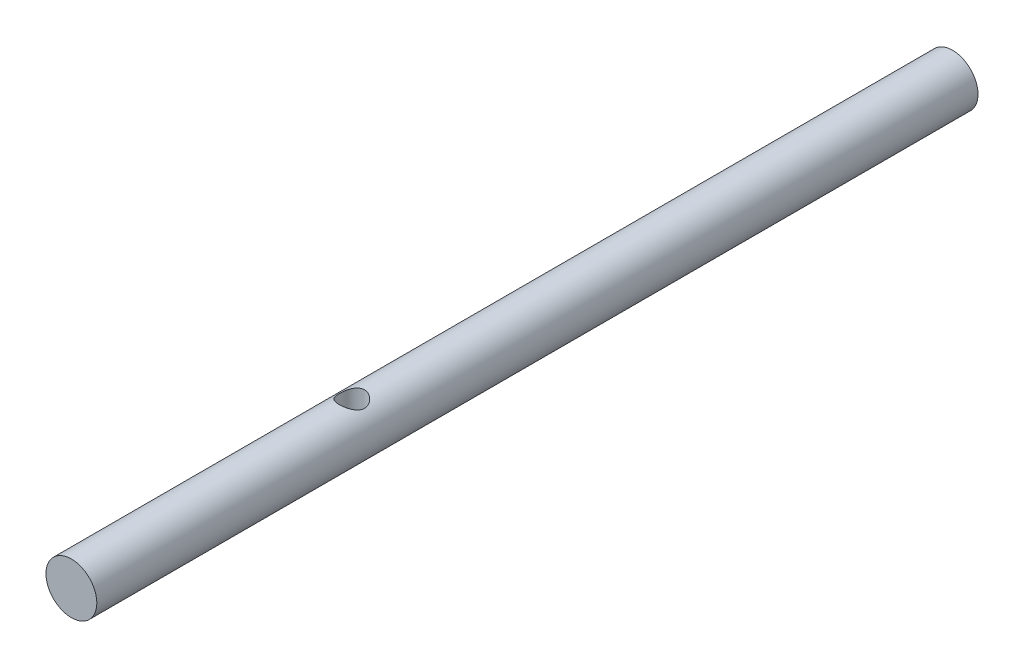
SolidWorks part; units mm, degrees
material "Plain Carbon Steel"
ref_plane "Front Plane" through (0, 0, 0) normal (0, 0, 1) x (1, 0, 0)
ref_plane "Top Plane" through (0, 0, 0) normal (0, 1, 0) x (1, 0, 0)
ref_plane "Right Plane" through (0, 0, 0) normal (1, 0, 0) x (0, 0, -1)
sketch "Sketch1" plane through (0, 0, 0) normal (0, 0, 1) x (1, 0, 0)
  circle A0 centre (0, 0) radius 1.5875
  dimension "D1" = 3.175
extrude "Boss-Extrude1" add sketch "Sketch1" along normal mid plane 55
sketch "Sketch2" plane through (0, 0, 0) normal (0, 1, 0) x (1, 0, 0)
  line L0 (-1.5875, -27.5) -> (1.5875, -27.5) construction
  circle A0 centre (0, -10) radius 0.7937
  dimension "D1" = 1.5875
  dimension "D2" = 17.5
extrude "Cut-Extrude1" cut sketch "Sketch2" against normal through all and the other way through all
